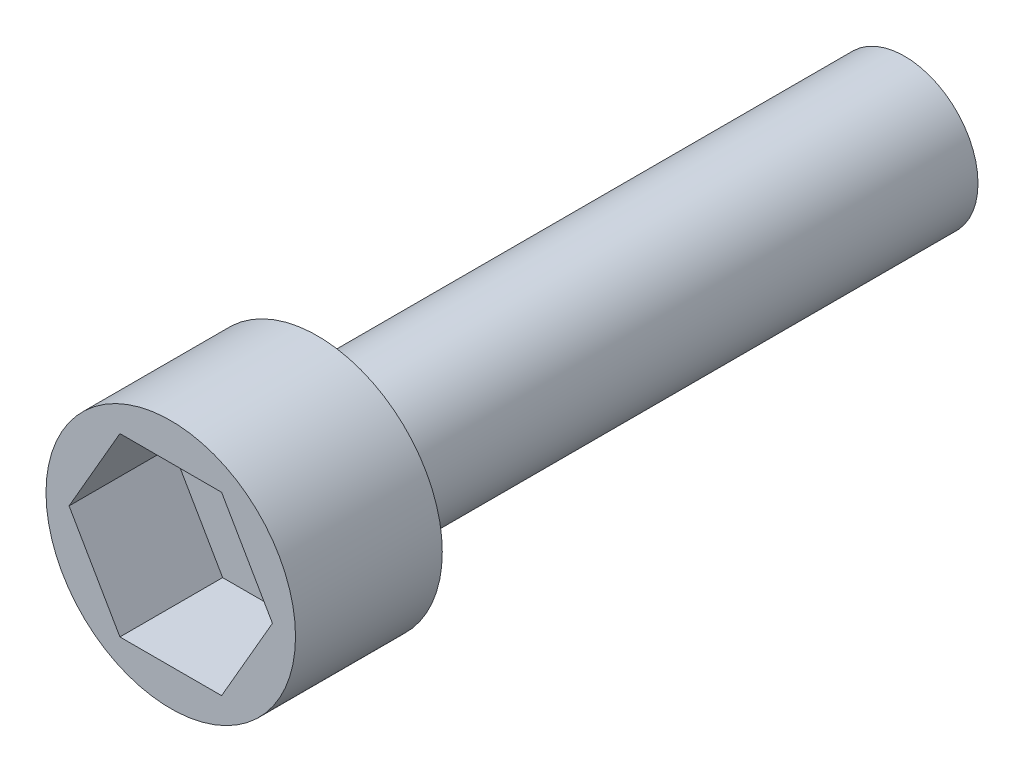
SolidWorks part; units mm, degrees
ref_plane "Plan de face" through (0, 0, 0) normal (0, 0, 1) x (1, 0, 0)
ref_plane "Plan de dessus" through (0, 0, 0) normal (0, 1, 0) x (1, 0, 0)
ref_plane "Plan de droite" through (0, 0, 0) normal (1, 0, 0) x (0, 0, -1)
sketch "Esquisse1" plane through (0, 0, 0) normal (0, 0, 1) x (1, 0, 0)
  circle A0 centre (0, 0) radius 2.5
  dimension "D1" = 5
extrude "Boss.-Extru.1" add sketch "Esquisse1" along normal blind 20
sketch "Esquisse2" plane through (0, 0, 20) normal (0, 0, 1) x (1, 0, 0)
  circle A0 centre (0, 0) radius 4.25
  dimension "D1" = 8.5
extrude "Boss.-Extru.2" add sketch "Esquisse2" along normal blind 5
sketch "Esquisse3" plane through (0, 0, 25) normal (0, 0, 1) x (1, 0, 0)
  line L1 (3.4641, 0) -> (1.7321, 3)
  line L2 (1.7321, 3) -> (-1.7321, 3)
  line L3 (-1.7321, 3) -> (-3.4641, 0)
  line L4 (-3.4641, 0) -> (-1.7321, -3)
  line L5 (-1.7321, -3) -> (1.7321, -3)
  line L6 (1.7321, -3) -> (3.4641, 0)
  circle A0 centre (0, 0) radius 3 construction
  dimension "D1" = 6
extrude "Enlèv. mat.-Extru.1" cut sketch "Esquisse3" against normal blind 3.5
